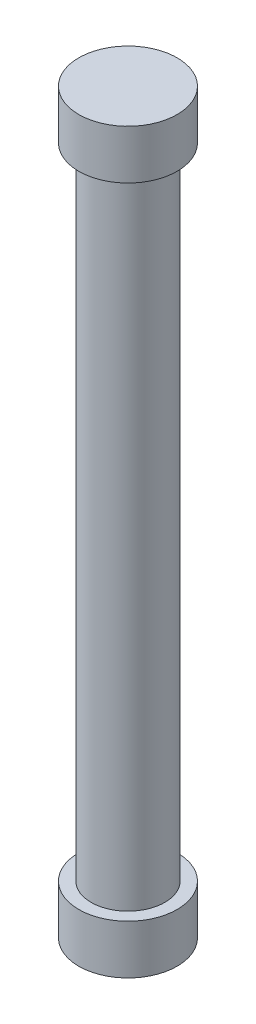
SolidWorks part; units mm, degrees
material "6061-T6 (SS)"
ref_plane "Front Plane" through (0, 0, 0) normal (0, 0, 1) x (1, 0, 0)
ref_plane "Top Plane" through (0, 0, 0) normal (0, 1, 0) x (1, 0, 0)
ref_plane "Right Plane" through (0, 0, 0) normal (1, 0, 0) x (0, 0, -1)
sketch "Sketch1" plane through (0, 0, 0) normal (0, 0, 1) x (1, 0, 0)
  line L0 (0, 15) -> (0, -15)
  line L1 (0, -15) -> (-2, -15)
  line L2 (-2, -15) -> (-2, -13)
  line L3 (-2, -13) -> (-1.5, -13)
  line L4 (-1.5, -13) -> (-1.5, 13)
  line L5 (-1.5, 13) -> (-2, 13)
  line L6 (-2, 13) -> (-2, 15)
  line L7 (-2, 15) -> (0, 15)
  dimension "D1" = 1.5
  dimension "D2" = 2
  dimension "D3" = 2
  dimension "D4" = 2
  dimension "D5" = 2
  dimension "D6" = 30
revolve "Revolve1" add sketch "Sketch1" angle 360 about L0
